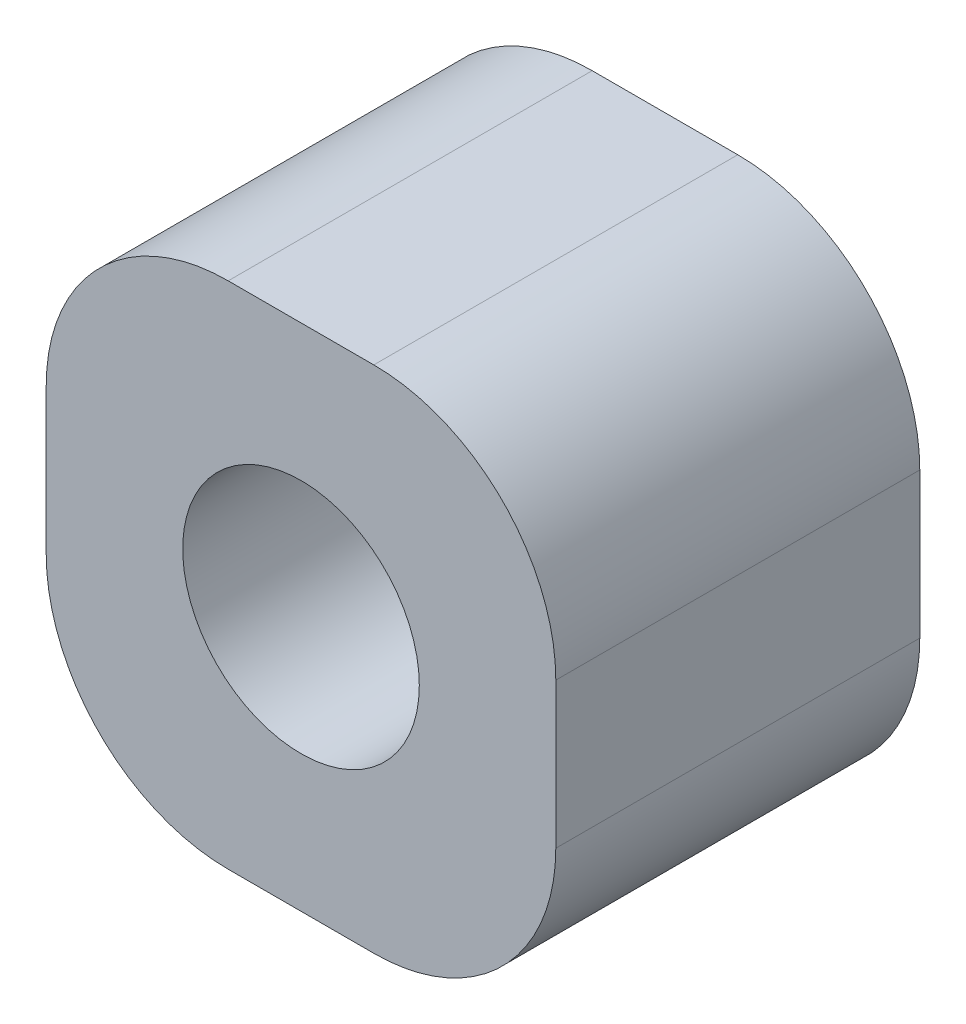
SolidWorks part; units mm, degrees
ref_plane "Front Plane" through (0, 0, 0) normal (0, 0, 1) x (1, 0, 0)
ref_plane "Top Plane" through (0, 0, 0) normal (0, 1, 0) x (1, 0, 0)
ref_plane "Right Plane" through (0, 0, 0) normal (1, 0, 0) x (0, 0, -1)
sketch "Sketch1" plane through (0, 0, 0) normal (0, 0, 1) x (1, 0, 0)
  line L1 (0, 0) -> (14, 0)
  line L2 (0, 0) -> (0, 14)
  line L3 (0, 14) -> (14, 14)
  line L4 (14, 0) -> (14, 14)
  circle A0 centre (7, 7) radius 3.25
  dimension "D3" = 6.5
  dimension "D4" = 7
  dimension "D1" = 14
  dimension "D2" = 14
  dimension "D5" = 7
extrude "Boss-Extrude1" add sketch "Sketch1" along normal blind 10
fillet "Fillet1" radius 5 4 edges at (14, 14, 5) (14, 0, 5) (0, 0, 5) (0, 14, 5)
